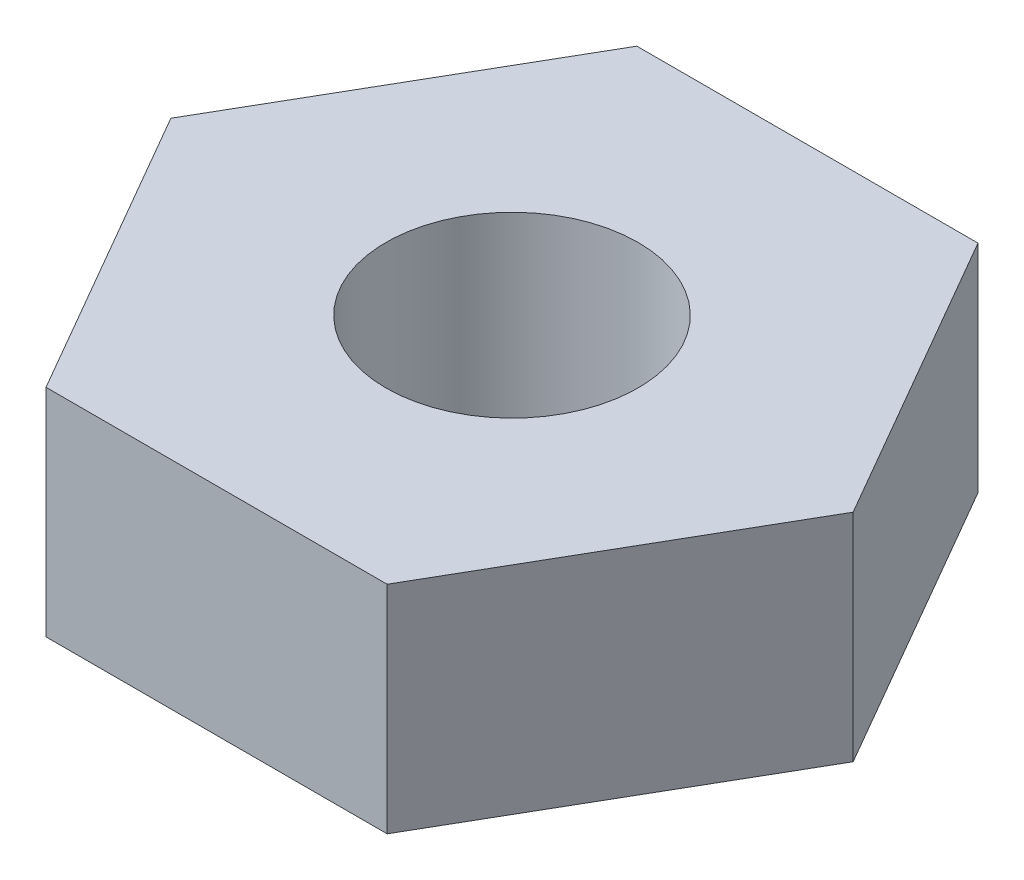
SolidWorks part; units mm, degrees
ref_plane "Alzado" through (0, 0, 0) normal (0, 0, 1) x (1, 0, 0)
ref_plane "Planta" through (0, 0, 0) normal (0, 1, 0) x (1, 0, 0)
ref_plane "Vista lateral" through (0, 0, 0) normal (1, 0, 0) x (0, 0, -1)
sketch "Croquis1" plane through (0, 0, 0) normal (0, 1, 0) x (1, 0, 0)
  line L1 (4.7343, 0) -> (2.3671, 4.1)
  line L2 (2.3671, 4.1) -> (-2.3671, 4.1)
  line L3 (-2.3671, 4.1) -> (-4.7343, 0)
  line L4 (-4.7343, 0) -> (-2.3671, -4.1)
  line L5 (-2.3671, -4.1) -> (2.3671, -4.1)
  line L6 (2.3671, -4.1) -> (4.7343, 0)
  circle A0 centre (0, 0) radius 1.75
  circle A1 centre (0, 0) radius 4.1 construction
  dimension "D1" = 3.5
  dimension "D2" = 8.2
extrude "Saliente-Extruir1" add sketch "Croquis1" along normal blind 3
